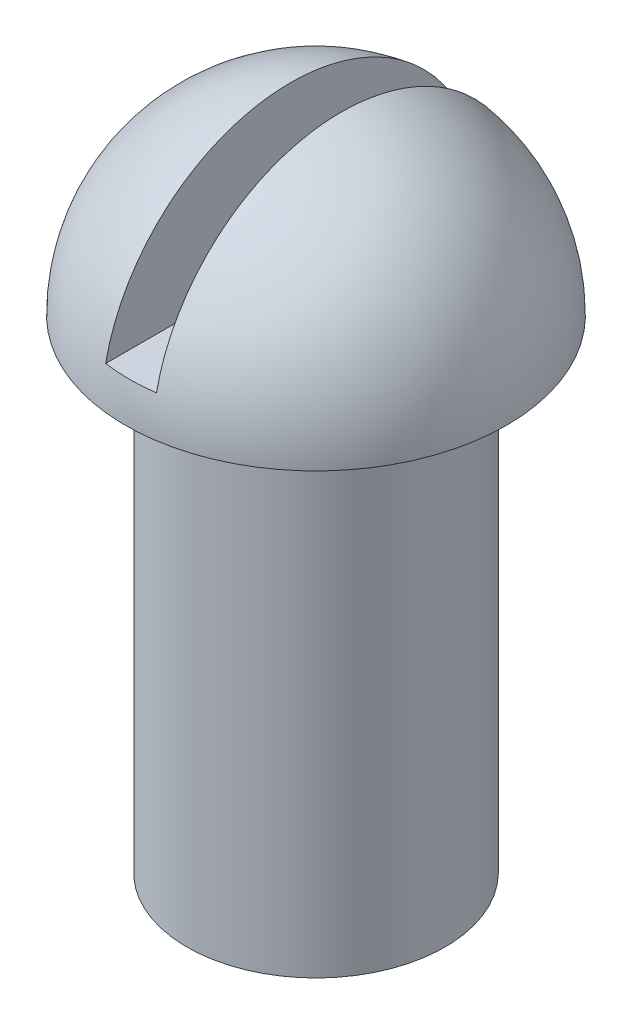
SolidWorks part; units mm, degrees
ref_plane "Front Plane" through (0, 0, 0) normal (0, 0, 1) x (1, 0, 0)
ref_plane "Top Plane" through (0, 0, 0) normal (0, 1, 0) x (1, 0, 0)
ref_plane "Right Plane" through (0, 0, 0) normal (1, 0, 0) x (0, 0, -1)
sketch "Sketch1" plane through (0, 0, 0) normal (0, 0, 1) x (1, 0, 0)
  line L0 (0, 53) -> (0, 0)
  line L1 (15, 38) -> (10.15, 38)
  line L2 (10.15, 38) -> (10.15, 0)
  line L3 (10.15, 0) -> (0, 0)
  arc A0 (15, 38) -> (0, 53) centre (0, 38) ccw
  point P3 (0, 0)
  point P8 (0, 0)
  dimension "D1" = 15
  dimension "D2" = 38
  dimension "D3" = 10.15
revolve "Revolve1" add sketch "Sketch1" angle 360 about L0
sketch "Sketch2" plane through (0, 0, 0) normal (0, 0, 1) x (1, 0, 0)
  line L0 (0, 0) -> (0, 34.1902) construction
  line L1 (-2, 41) -> (2, 41)
  line L2 (-2, 41) -> (-2, 52.8661)
  line L4 (2, 41) -> (2, 52.8661)
  line L5 (-10.15, 0) -> (10.15, 0) construction
  line L6 (-10.15, 38) -> (10.15, 38) construction
  arc A1 (15, 38) -> (-15, 38) centre (0, 38) ccw construction
  arc A3 (2, 52.8661) -> (-2, 52.8661) centre (0, 38) ccw
  point P1 (0, 41)
  point P17 (15.7916, 39.8125)
  dimension "D1" = 4
  dimension "D2" = 3
extrude "Cut-Extrude1" cut sketch "Sketch2" against normal through all both and the other way through all
